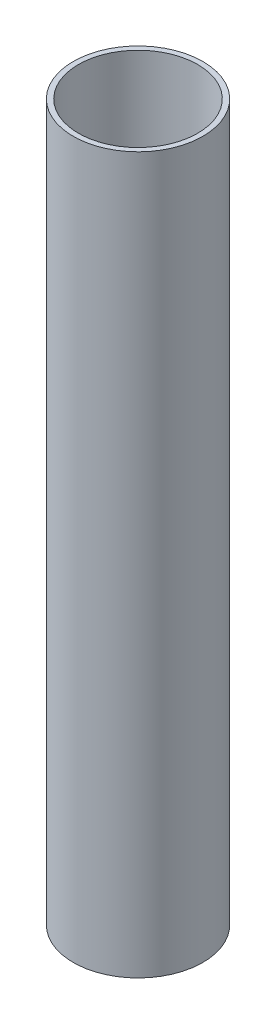
SolidWorks part; units mm, degrees
material "ABS"
ref_plane "Front Plane" through (0, 0, 0) normal (0, 0, 1) x (1, 0, 0)
ref_plane "Top Plane" through (0, 0, 0) normal (0, 1, 0) x (1, 0, 0)
ref_plane "Right Plane" through (0, 0, 0) normal (1, 0, 0) x (0, 0, -1)
sketch "Sketch1" plane through (0, 0, 0) normal (0, 1, 0) x (1, 0, 0)
  circle A0 centre (0, 0) radius 27.6225
  circle A1 centre (0, 0) radius 25.4
  dimension "D1" = 55.245
  dimension "D2" = 2.2225
extrude "Boss-Extrude1" add sketch "Sketch1" along normal blind 304.8
